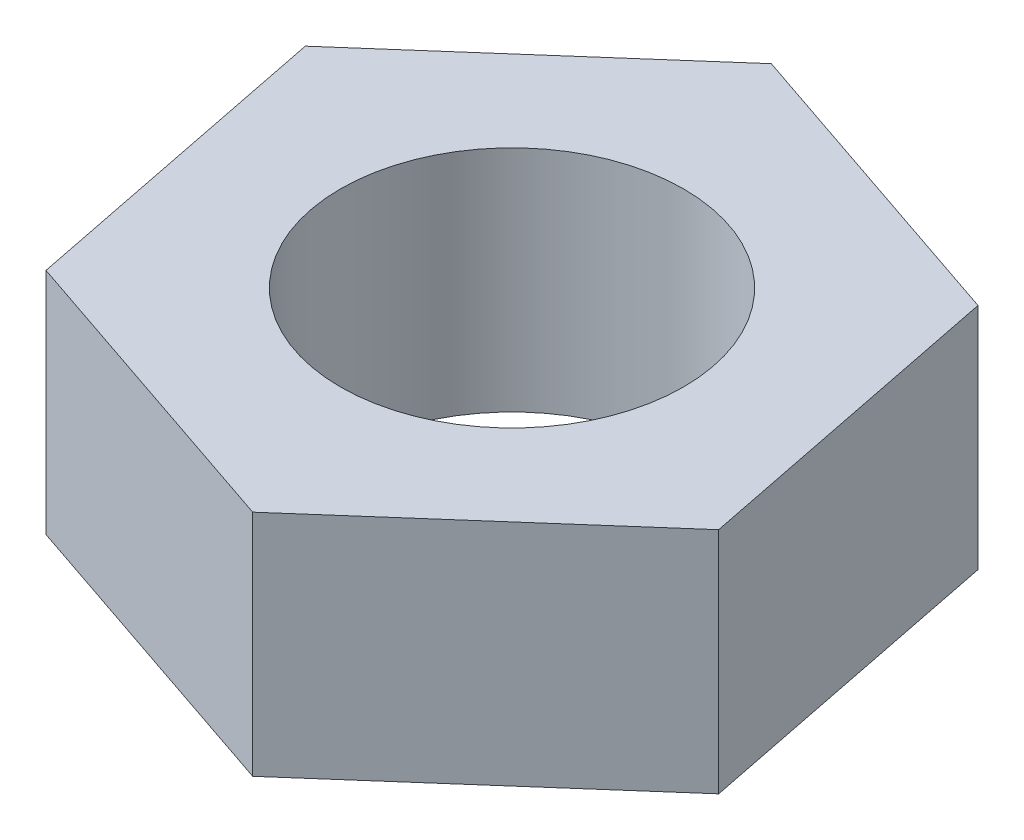
SolidWorks part; units mm, degrees
ref_plane "Front Plane" through (0, 0, 0) normal (0, 0, 1) x (1, 0, 0)
ref_plane "Top Plane" through (0, 0, 0) normal (0, 1, 0) x (1, 0, 0)
ref_plane "Right Plane" through (0, 0, 0) normal (1, 0, 0) x (0, 0, -1)
sketch "Sketch1" plane through (0, 0, 0) normal (0, 1, 0) x (1, 0, 0)
  line L13 (0, 12.5) -> (0.1674, 12.5)
  line L15 (10.8484, 9.5208) -> (-2.8211, 14.1554)
  line L16 (-2.8211, 14.1554) -> (-13.6695, 4.6345)
  line L17 (-13.6695, 4.6345) -> (-10.8484, -9.5208)
  line L18 (-10.8484, -9.5208) -> (2.8211, -14.1554)
  line L19 (2.8211, -14.1554) -> (13.6695, -4.6345)
  line L20 (13.6695, -4.6345) -> (10.8484, 9.5208)
  circle A1 centre (0, 0) radius 7.5
  point P1 (0, 0)
  dimension "D1" = 12.5
  dimension "D2" = 15
extrude "Boss-Extrude1" add sketch "Sketch1" along normal blind 10
